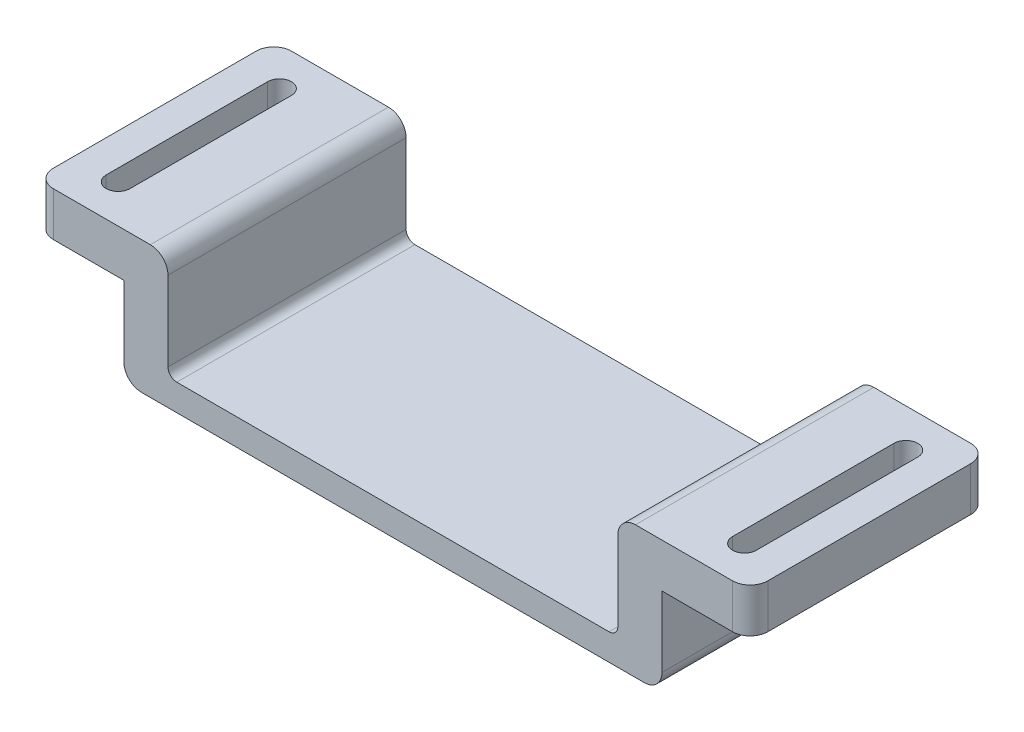
SolidWorks part; units mm, degrees
ref_plane "Front Plane" through (0, 0, 0) normal (0, 0, 1) x (1, 0, 0)
ref_plane "Top Plane" through (0, 0, 0) normal (0, 1, 0) x (1, 0, 0)
ref_plane "Right Plane" through (0, 0, 0) normal (1, 0, 0) x (0, 0, -1)
sketch "Sketch1" plane through (0, 0, 0) normal (0, 1, 0) x (1, 0, 0)
  line L1 (0, 0) -> (61, 0)
  line L2 (0, 0) -> (0, 27)
  line L3 (0, 27) -> (61, 27)
  line L4 (61, 0) -> (61, 27)
  dimension "D1" = 61
  dimension "D2" = 27
extrude "Boss-Extrude1" add sketch "Sketch1" along normal blind 3
sketch "Sketch2" plane through (0, 3, 0) normal (0, 1, 0) x (1, 0, 0)
  line L0 (0, 0) -> (61, 0) construction
  line L1 (0, 27) -> (5, 27)
  line L2 (0, 27) -> (0, 0)
  line L3 (0, 0) -> (5, 0)
  line L4 (5, 27) -> (5, 0)
  line L6 (61, 27) -> (56, 27)
  line L7 (61, 27) -> (61, 0)
  line L8 (61, 0) -> (56, 0)
  line L9 (56, 27) -> (56, 0)
  dimension "D1" = 5
  dimension "D2" = 5
extrude "Boss-Extrude2" add sketch "Sketch2" along normal blind 7
sketch "Sketch3" plane through (0, 10, 0) normal (0, 1, 0) x (1, 0, 0)
  line L1 (5, 27) -> (-10, 27)
  line L2 (5, 27) -> (5, 0)
  line L3 (5, 0) -> (-10, 0)
  line L4 (-10, 27) -> (-10, 0)
  line L5 (56, 27) -> (71, 27)
  line L6 (56, 27) -> (56, 0)
  line L7 (56, 0) -> (71, 0)
  line L8 (71, 27) -> (71, 0)
  dimension "D1" = 15
  dimension "D2" = 15
extrude "Boss-Extrude3" add sketch "Sketch3" along normal blind 5
sketch "Sketch4" plane through (0, 10, 0) normal (0, -1, 0) x (1, 0, 0)
  line L0 (-5, 0) -> (-5, -27) construction
  line L1 (-10, 0) -> (0, 0) construction
  line L2 (0, -27) -> (-10, -27) construction
  line L3 (66, 0) -> (66, -27) construction
  line L4 (61, 0) -> (71, 0) construction
  line L5 (71, -27) -> (61, -27) construction
  line L6 (-5, -4.35) -> (-5, -22.65) construction
  line L7 (-3.65, -4.35) -> (-3.65, -22.65)
  line L8 (-6.35, -4.35) -> (-6.35, -22.65)
  line L9 (66, -4.35) -> (66, -22.65) construction
  line L10 (67.35, -4.35) -> (67.35, -22.65)
  line L11 (64.65, -4.35) -> (64.65, -22.65)
  arc A0 (-3.65, -4.35) -> (-6.35, -4.35) centre (-5, -4.35) ccw
  arc A1 (-6.35, -22.65) -> (-3.65, -22.65) centre (-5, -22.65) ccw
  arc A2 (67.35, -4.35) -> (64.65, -4.35) centre (66, -4.35) ccw
  arc A3 (64.65, -22.65) -> (67.35, -22.65) centre (66, -22.65) ccw
  point P14 (-5, -13.5)
  point P19 (-5, -3)
  point P20 (-5, -24)
  point P23 (66, -13.5)
  point P28 (66, -3)
  point P29 (66, -24)
  dimension "D1" = 2.7
  dimension "D2" = 3
  dimension "D3" = 3
  dimension "D4" = 3
  dimension "D5" = 3
  dimension "D6" = 2.7
extrude "Cut-Extrude1" cut sketch "Sketch4" against normal through all
fillet "Fillet1" radius 2 4 edges at (71, 12.5, 0) (71, 12.5, -27) (-10, 12.5, -27) (-10, 12.5, 0)
fillet "Fillet2" radius 2 4 edges at (0, 0, -13.5) (5, 15, -13.5) (61, 0, -13.5) (56, 15, -13.5)
fillet "Fillet3" radius 1 2 edges at (5, 3, -13.5) (56, 3, -13.5)
